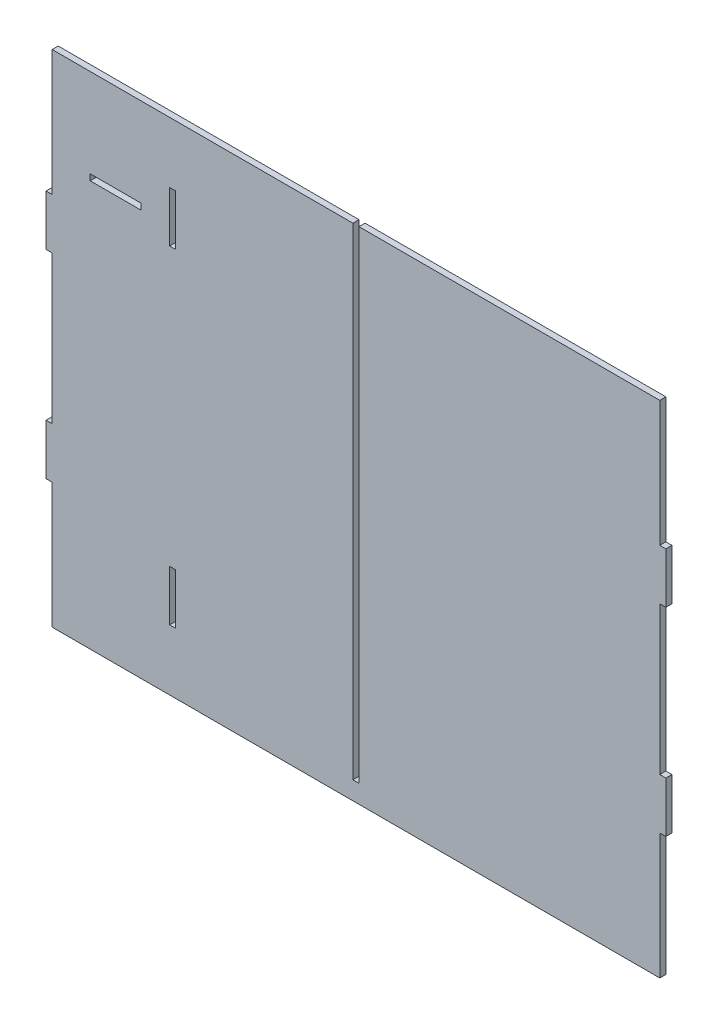
SolidWorks part; units mm, degrees
material "Maple"
ref_plane "Front Plane" through (0, 0, 0) normal (0, 0, 1) x (1, 0, 0)
ref_plane "Top Plane" through (0, 0, 0) normal (0, 1, 0) x (1, 0, 0)
ref_plane "Right Plane" through (0, 0, 0) normal (1, 0, 0) x (0, 0, -1)
sketch "Sketch1" plane through (0, 0, 0) normal (0, 0, 1) x (1, 0, 0)
  line L6 (300, -476) -> (300, 0) construction
  line L55 (0, 0) -> (297, 0)
  line L56 (0, 0) -> (0, -124)
  line L57 (0, -494) -> (600, -494)
  line L58 (600, 0) -> (600, -124)
  line L64 (297, 0) -> (297, -476)
  line L65 (297, -476) -> (303, -476)
  line L77 (303, 0) -> (303, -476)
  line L78 (303, 0) -> (600, 0)
  line L79 (300, -247) -> (297, -247) construction
  line L81 (116, -384) -> (122, -384)
  line L82 (116, -60) -> (122, -60)
  line L83 (116, -60) -> (116, -110)
  line L84 (116, -110) -> (122, -110)
  line L85 (122, -60) -> (122, -110)
  line L86 (116, -60) -> (122, -110) construction
  line L87 (116, -110) -> (122, -60) construction
  line L88 (122, -434) -> (122, -384)
  line L89 (116, -434) -> (122, -434)
  line L90 (116, -434) -> (116, -384)
  line L103 (0, -174) -> (-6, -174)
  line L104 (37.5, -87.5) -> (87.5, -87.5)
  line L105 (37.5, -87.5) -> (37.5, -93.5)
  line L106 (37.5, -93.5) -> (87.5, -93.5)
  line L107 (87.5, -87.5) -> (87.5, -93.5)
  line L108 (37.5, -87.5) -> (87.5, -93.5) construction
  line L109 (37.5, -93.5) -> (87.5, -87.5) construction
  line L110 (600, -124) -> (606, -124)
  line L112 (600, -174) -> (606, -174)
  line L113 (606, -124) -> (606, -174)
  line L114 (600, -370) -> (600, -494)
  line L116 (-6, -124) -> (-6, -174)
  line L117 (0, -124) -> (-6, -124)
  line L119 (600, -320) -> (606, -320)
  line L120 (606, -370) -> (606, -320)
  line L121 (600, -370) -> (606, -370)
  line L124 (0, -370) -> (-6, -370)
  line L125 (-6, -370) -> (-6, -320)
  line L126 (0, -320) -> (-6, -320)
  line L127 (0, -370) -> (0, -494)
  line L128 (0, -174) -> (0, -320)
  line L129 (600, -174) -> (600, -320)
  point P0 (-416.8486, 134.664)
  point P12 (119, -60)
  point P15 (125, -84.5)
  point P25 (75, -241)
  point P34 (62.5, -90.5)
  point P41 (600, -43)
  dimension "D2" = 600
  dimension "D3" = 18
  dimension "D4" = 300
  dimension "D5" = 6
  dimension "D6" = 300
  dimension "D7" = 6
  dimension "D8" = 50
  dimension "D9" = 297
  dimension "D10" = 300
  dimension "D11" = 50
  dimension "D12" = 28.5
  dimension "D13" = 6
  dimension "D14" = 6
  dimension "D15" = 50
  dimension "D16" = 124
  dimension "D17" = 124
  dimension "D18" = 37.5
  dimension "D19" = 146
  dimension "D20" = 494
  dimension "D21" = 60
  dimension "D22" = 60
extrude "Boss-Extrude1" add sketch "Sketch1" along normal blind 6
